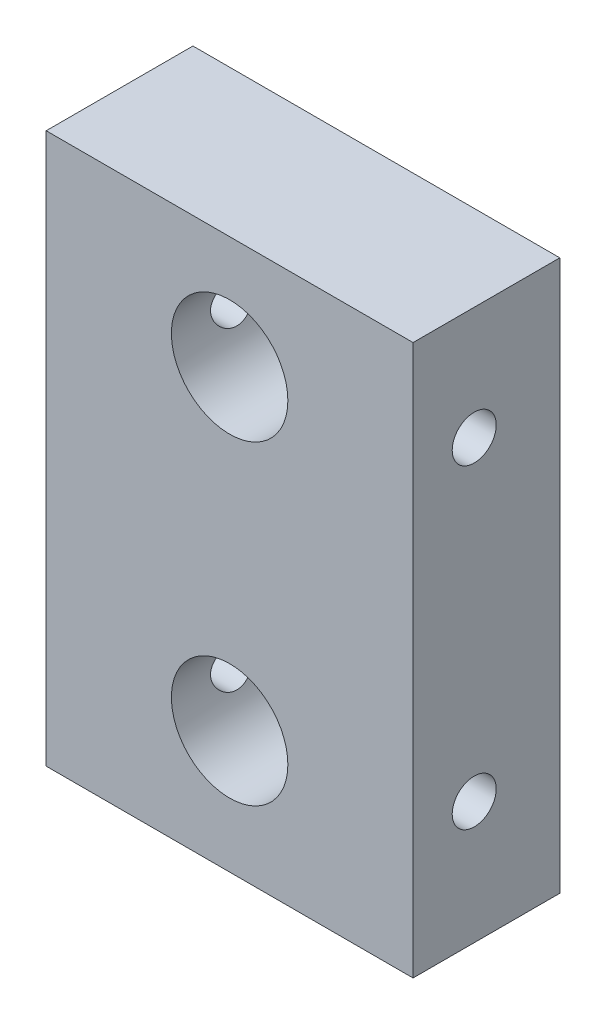
SolidWorks part; units mm, degrees
material "Náilon 6/10"
ref_plane "Plano frontal" through (0, 0, 0) normal (0, 0, 1) x (1, 0, 0)
ref_plane "Plano superior" through (0, 0, 0) normal (0, 1, 0) x (1, 0, 0)
ref_plane "Plano direito" through (0, 0, 0) normal (1, 0, 0) x (0, 0, -1)
sketch "Esboço1" plane through (0, 0, -196.3059) normal (0, 0, 1) x (1, 0, 0)
  line L1 (3.7648, 39.2324) -> (33.7648, 39.2324)
  line L2 (3.7648, 39.2324) -> (3.7648, -5.7676)
  line L3 (3.7648, -5.7676) -> (33.7648, -5.7676)
  line L4 (33.7648, 39.2324) -> (33.7648, -5.7676)
  circle A0 centre (18.7648, 30.0024) radius 4.7625
  circle A1 centre (18.7648, 4.2324) radius 4.7625
  dimension "D3" = 9.525
  dimension "D4" = 9.525
  dimension "D6" = 10
  dimension "D1" = 30
  dimension "D2" = 45
  dimension "D5" = 9.23
  dimension "D7" = 15
  dimension "D8" = 15
extrude "Ressalto-extrusão1" add sketch "Esboço1" along normal blind 12
hole_wizard "Furo com folga de M31" positions "Esboço3" profile "Esboço2" hole size "M3" standard "Métrico Ansi"
sketch "Esboço3" plane through (3.7648, 0, 0) normal (-1, 0, 0) x (0, 0, 1)
  line L0 (-184.3059, 39.2324) -> (-196.3059, 39.2324) construction
  line L1 (-184.3059, 39.2324) -> (-184.3059, -5.7676) construction
  point P0 (-189.3059, 30.0024)
  point P1 (-189.3059, 4.2324)
  dimension "D1" = 9.23
  dimension "D2" = 5
  dimension "D3" = 35
  dimension "D4" = 5
sketch "Esboço2" plane through (3.7648, 30.0024, -189.3059) normal (0, 1, 0) x (0, 0, 1)
  line L0 (0, 0) -> (0, 31.0815)
  line L1 (0, 31.0815) -> (1.8, 30)
  line L2 (1.8, 30) -> (1.8, 0)
  line L5 (1.8, 0) -> (0, 0)
  line L10 (0, 31.0815) -> (-1.8, 30) construction
  line L11 (0, -6.35) -> (0, 107.95) construction
  dimension "Hole Dia." = 3.6
  dimension "Hole Depth" = 30
  dimension "Drill Angle" = 118
